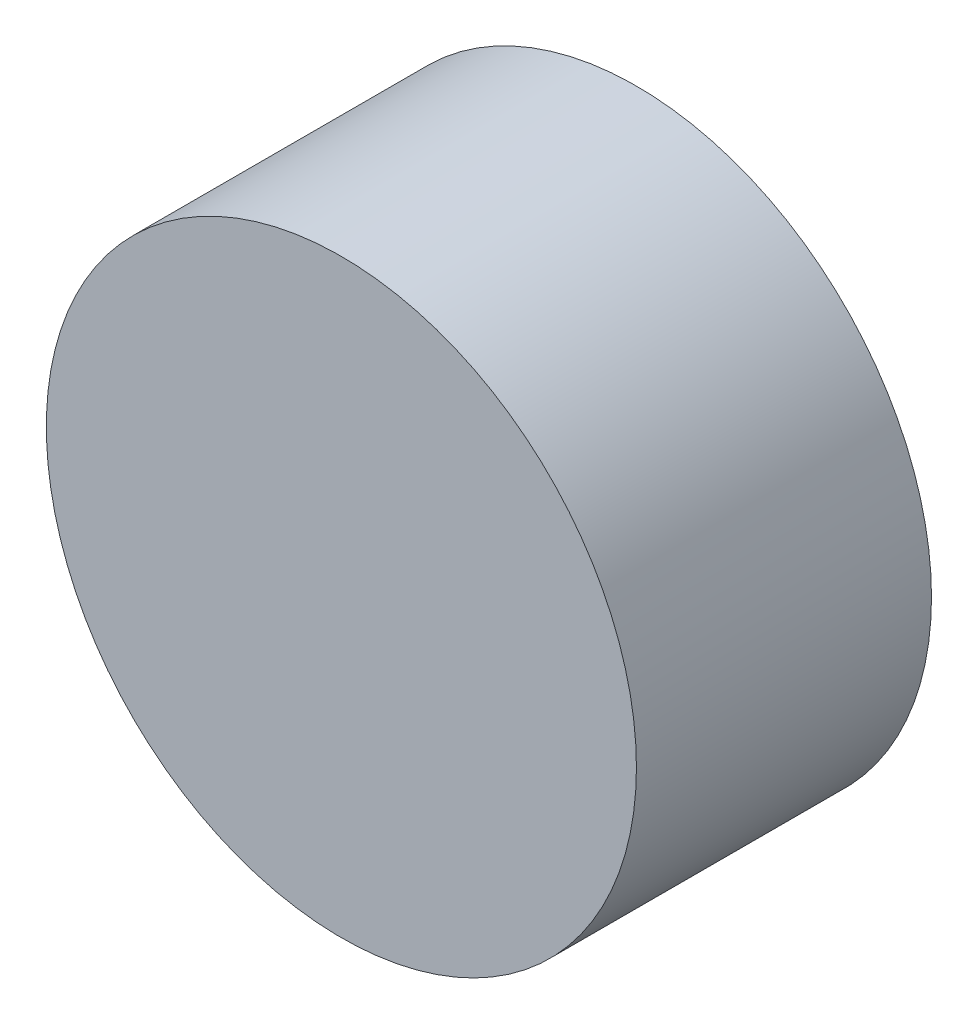
SolidWorks part; units mm, degrees
ref_plane "Front Plane" through (0, 0, 0) normal (0, 0, 1) x (1, 0, 0)
ref_plane "Top Plane" through (0, 0, 0) normal (0, 1, 0) x (1, 0, 0)
ref_plane "Right Plane" through (0, 0, 0) normal (1, 0, 0) x (0, 0, -1)
sketch "Sketch1" plane through (0, 0, 0) normal (0, 0, 1) x (1, 0, 0)
  circle A0 centre (7, 7) radius 7
  dimension "D1" = 14
extrude "Profile" add sketch "Sketch1" along normal blind 7
equation "\"Profile_Depth\" = 7mm"
equation "\"D1@Profile\" = \"Profile_Depth\""
equation "\"EnvelopeWidth\" = 14mm"
equation "\"EnvelopeHeight\" = 14mm"
